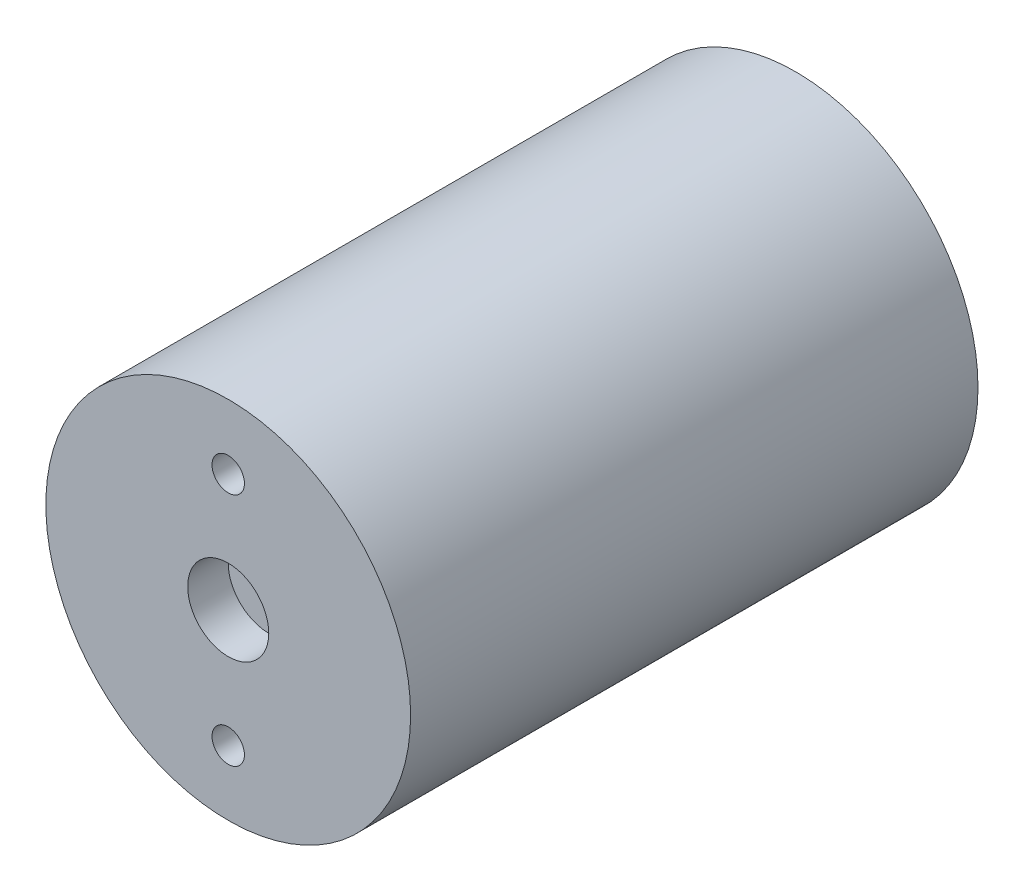
SolidWorks part; units mm, degrees
ref_plane "前视基准面" through (0, 0, 0) normal (0, 0, 1) x (1, 0, 0)
ref_plane "上视基准面" through (0, 0, 0) normal (0, 1, 0) x (1, 0, 0)
ref_plane "右视基准面" through (0, 0, 0) normal (1, 0, 0) x (0, 0, -1)
sketch "草图1" plane through (0, 0, 0) normal (0, 0, 1) x (1, 0, 0)
  circle A0 centre (0, 0) radius 22.5
  dimension "D1" = 45
extrude "凸台-拉伸1" add sketch "草图1" along normal blind 70
sketch "草图2" plane through (0, 0, 70) normal (0, 0, 1) x (1, 0, 0)
  arc A0 (-17.3214, -2.4936) -> (-2.4936, -17.3214) centre (0, 0) ccw construction
  arc A6 (17.3214, 2.4936) -> (-17.3214, 2.4936) centre (0, 0) ccw construction
  circle A8 centre (0, 14.5) radius 2
  arc A9 (2.4936, -17.3214) -> (17.3214, -2.4936) centre (0, 0) ccw construction
  circle A10 centre (0, -14.5) radius 2
  point P14 (0, 0)
  dimension "D1" = 35
extrude "切除-拉伸1" cut sketch "草图2" against normal blind 10
cosmetic thread "装饰螺纹线1" parameters "D2"=5
sketch "草图4" plane through (0, 0, 0) normal (0, 0, -1) x (-1, 0, 0)
  circle A0 centre (0, 0) radius 5
  dimension "D1" = 10
sketch "草图5" plane through (0, 0, 70) normal (0, 0, 1) x (1, 0, 0)
  circle A0 centre (0, 0) radius 5
  dimension "D1" = 10
extrude "切除-拉伸2" cut sketch "草图5" against normal blind 5
